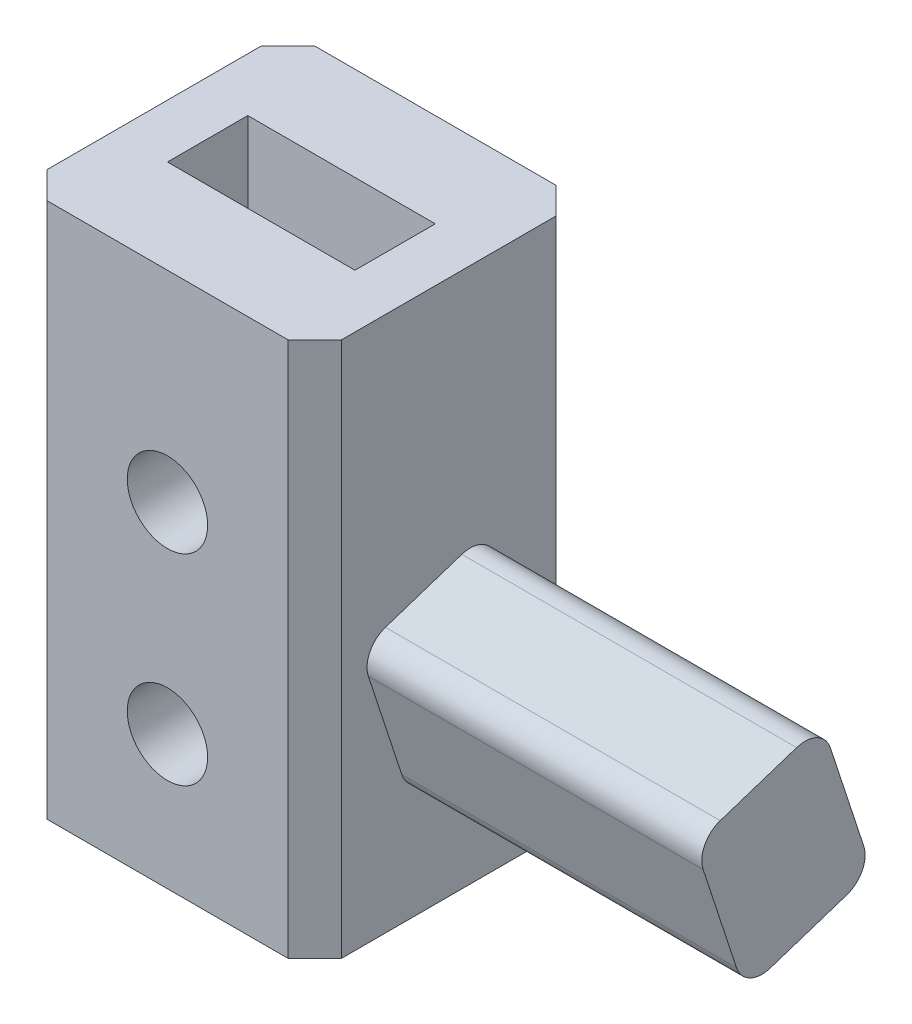
SolidWorks part; units mm, degrees
ref_plane "Alzado" through (0, 0, 0) normal (0, 0, 1) x (1, 0, 0)
ref_plane "Planta" through (0, 0, 0) normal (0, 1, 0) x (1, 0, 0)
ref_plane "Vista lateral" through (0, 0, 0) normal (1, 0, 0) x (0, 0, -1)
sketch "Croquis1" plane through (0, 0, 0) normal (0, 1, 0) x (1, 0, 0)
  line L0 (-11, 8) -> (-9, 10)
  line L1 (-50, 0) -> (0, 0) construction
  line L2 (0, 0) -> (50, 0) construction
  line L3 (9, -10) -> (-9, -10)
  line L4 (11, -8) -> (11, 8)
  line L5 (9, 10) -> (-9, 10)
  line L6 (-11, -8) -> (-11, 8)
  line L7 (11, -10) -> (-11, 10) construction
  line L8 (11, 10) -> (-11, -10) construction
  line L9 (7, -3) -> (-7, -3)
  line L10 (7, -3) -> (7, 3)
  line L11 (7, 3) -> (-7, 3)
  line L12 (-7, -3) -> (-7, 3)
  line L13 (7, -3) -> (-7, 3) construction
  line L14 (7, 3) -> (-7, -3) construction
  line L15 (11, 8) -> (9, 10)
  line L16 (-9, -10) -> (-11, -8)
  line L17 (11, -8) -> (9, -10)
  dimension "D1" = 50
  dimension "D2" = 22
  dimension "D3" = 20
  dimension "D4" = 14
  dimension "D5" = 6
extrude "Saliente-Extruir1" add sketch "Croquis1" along normal blind 40
sketch "Croquis2" plane through (11, 0, 0) normal (1, 0, 0) x (0, 0, -1)
  line L0 (0, 0) -> (0, 40) construction
  line L1 (-8, 40) -> (8, 40) construction
  line L2 (0, 15) -> (13.2446, 19.8206) construction
  line L3 (0, 15) -> (-7.6451, 36.0048) construction
  line L4 (-3.5051, 9.6414) -> (-5.9973, 17.2434)
  line L5 (-0.9816, 8.364) -> (4.7198, 10.2331)
  line L6 (-4.7198, 19.7669) -> (0.9816, 21.636)
  line L7 (5.9973, 12.7566) -> (3.5051, 20.3586)
  line L8 (-2.8821, 7.741) -> (2.8821, 22.259) construction
  line L9 (-6.6203, 19.1438) -> (6.6203, 10.8562) construction
  arc A0 (-4.7198, 19.7669) -> (-5.9973, 17.2434) centre (-4.0968, 17.8664) ccw
  arc A1 (3.5051, 20.3586) -> (0.9816, 21.636) centre (1.6046, 19.7355) ccw
  arc A2 (4.7198, 10.2331) -> (5.9973, 12.7566) centre (4.0968, 12.1336) ccw
  arc A3 (-3.5051, 9.6414) -> (-0.9816, 8.364) centre (-1.6046, 10.2645) ccw
  dimension "D4" = 2
  dimension "D5" = 2
  dimension "D6" = 2
  dimension "D7" = 2
  dimension "D1" = 20
  dimension "D2" = 12
  dimension "D3" = 10
extrude "Saliente-Extruir4" add sketch "Croquis2" along normal blind 25
sketch "Croquis3" plane through (0, 0, 10) normal (0, 0, 1) x (1, 0, 0)
  line L0 (0, 0) -> (0, 40) construction
  line L1 (-9, 40) -> (9, 40) construction
  circle A0 centre (0, 10) radius 3
  circle A1 centre (0, 25) radius 3
  dimension "D2" = 6
  dimension "D4" = 6
  dimension "D1" = 10
  dimension "D3" = 25
extrude "Cortar-Extruir1" cut sketch "Croquis3" against normal up to next
